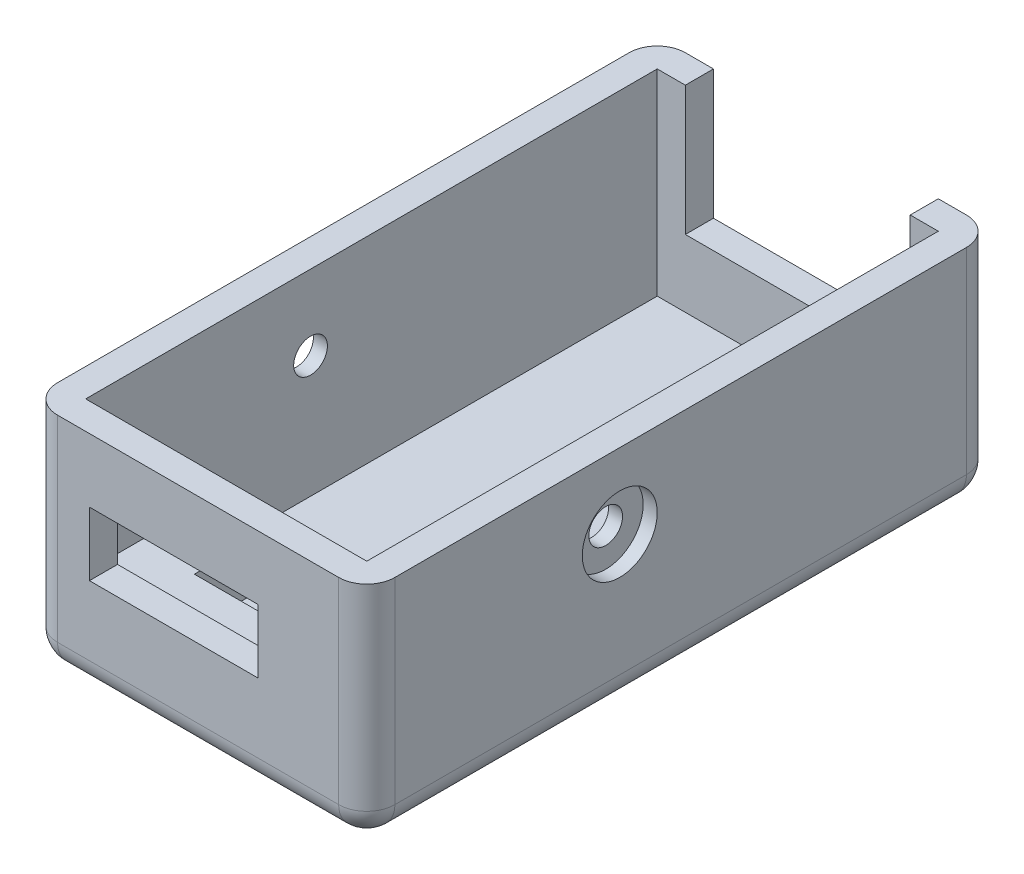
SolidWorks part; units mm, degrees
ref_plane "前视基准面" through (0, 0, 0) normal (0, 0, 1) x (1, 0, 0)
ref_plane "上视基准面" through (0, 0, 0) normal (0, 1, 0) x (1, 0, 0)
ref_plane "右视基准面" through (0, 0, 0) normal (1, 0, 0) x (0, 0, -1)
sketch "草图1" plane through (0, 0, 0) normal (0, 1, 0) x (1, 0, 0)
  line L1 (-9, 16.75) -> (9, 16.75)
  line L2 (-9, 16.75) -> (-9, -16.75)
  line L3 (-9, -16.75) -> (9, -16.75)
  line L4 (9, 16.75) -> (9, -16.75)
  dimension "D1" = 33.5
  dimension "D2" = 18
  dimension "D3" = 9
  dimension "D4" = 16.75
extrude "凸台-拉伸1" add sketch "草图1" along normal blind 12
shell "抽壳1" thickness 1.5
fillet "圆角1" radius 1.5 8 edges at (-9, 0, 0) (0, 0, 16.75) (0, 0, -16.75) (9, 0, 0) (9, 6, -16.75) (9, 6, 16.75) (-9, 6, 16.75) (-9, 6, -16.75)
sketch "草图2" plane through (0, 1.5, 0) normal (0, 1, 0) x (1, 0, 0)
  line L0 (-7.5, 15.25) -> (-7.5, -15.25) construction
  line L1 (-7.5, -9.95) -> (7.5, -9.95)
  line L2 (-7.5, -9.95) -> (-7.5, -15.25)
  line L3 (-7.5, -15.25) -> (7.5, -15.25)
  line L4 (7.5, -9.95) -> (7.5, -15.25)
  dimension "D1" = 5.3
extrude "凸台-拉伸2" add sketch "草图2" along normal blind 2.5
sketch "草图4" plane through (0, 4, 0) normal (0, 1, 0) x (1, 0, 0)
  line L1 (1.5, -9.95) -> (-4.5, -9.95)
  line L2 (1.5, -9.95) -> (1.5, -12.45)
  line L3 (1.5, -12.45) -> (-4.5, -12.45)
  line L4 (-4.5, -9.95) -> (-4.5, -12.45)
  line L5 (7.5, -9.95) -> (-7.5, -9.95) construction
  line L6 (-7.5, -9.95) -> (-7.5, -15.25) construction
  dimension "D1" = 6
  dimension "D2" = 3
  dimension "D3" = 2.5
  dimension "D4" = 0
extrude "切除-拉伸1" cut sketch "草图4" against normal blind 2.5
fillet "圆角3" radius 1.5 2 edges at (-6, 1.5, 9.95) (4.5, 1.5, 9.95)
sketch "草图5" plane through (0, 0, 15.25) normal (0, 0, -1) x (-1, 0, 0)
  line L1 (-3.2, 8.6) -> (5.8, 8.6)
  line L2 (-3.2, 8.6) -> (-3.2, 5.2)
  line L3 (-3.2, 5.2) -> (5.8, 5.2)
  line L4 (5.8, 8.6) -> (5.8, 5.2)
  line L5 (7.5, 4) -> (-7.5, 4) construction
  line L6 (7.5, 12) -> (7.5, 4) construction
  dimension "D1" = 3.4
  dimension "D2" = 1.7
  dimension "D3" = 9
  dimension "D4" = 1.2
extrude "切除-拉伸2" cut sketch "草图5" against normal blind 2.5
sketch "草图6" plane through (0, 0, -16.75) normal (0, 0, -1) x (-1, 0, 0)
  line L0 (-7.5, 1.5) -> (7.5, 1.5) construction
  line L1 (-6, 13.1) -> (6, 13.1)
  line L2 (-6, 13.1) -> (-6, 5.1)
  line L3 (-6, 5.1) -> (6, 5.1)
  line L4 (6, 13.1) -> (6, 5.1)
  dimension "D1" = 12
  dimension "D2" = 8
  dimension "D3" = 6
  dimension "D4" = 3.6
extrude "切除-拉伸3" cut sketch "草图6" against normal blind 2.5
sketch "草图7" plane through (0, 4, 0) normal (0, 1, 0) x (1, 0, 0)
  line L1 (-7.5, -15.25) -> (7.5, -15.25) construction
  line L2 (7.5, -15.25) -> (7.5, -9.95) construction
  circle A0 centre (5.3, -11.55) radius 0.9
  dimension "D3" = 1.8
  dimension "D1" = 2.2
  dimension "D2" = 3.7
extrude "切除-拉伸4" cut sketch "草图7" against normal blind 3
sketch "草图8" plane through (9, 0, 0) normal (1, 0, 0) x (0, 0, -1)
  line L0 (-15.25, 12) -> (15.25, 12) construction
  line L1 (-15.25, 12) -> (-15.25, 1.5) construction
  circle A0 centre (-3.25, 8) radius 0.9
  dimension "D1" = 4
  dimension "D2" = 12
extrude "切除-拉伸5" cut sketch "草图8" against normal blind 23.5
sketch "草图10" plane through (9, 0, 0) normal (1, 0, 0) x (0, 0, -1)
  circle A0 centre (-3.25, 8) radius 2
  dimension "D1" = 4
extrude "切除-拉伸7" cut sketch "草图10" against normal blind 0.75
sketch "草图11" plane through (-9, 0, 0) normal (-1, 0, 0) x (0, 0, 1)
  circle A0 centre (3.25, 8) radius 2
  dimension "D1" = 4
extrude "切除-拉伸8" cut sketch "草图11" against normal blind 0.75
